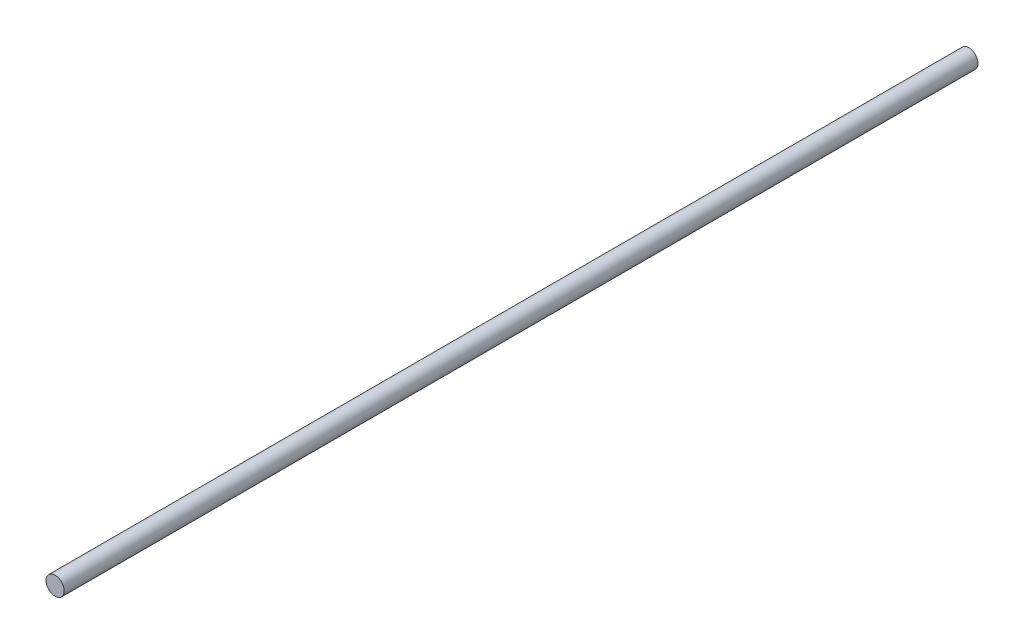
SolidWorks part; units mm, degrees
ref_plane "Front Plane" through (0, 0, 0) normal (0, 0, 1) x (1, 0, 0)
ref_plane "Top Plane" through (0, 0, 0) normal (0, 1, 0) x (1, 0, 0)
ref_plane "Right Plane" through (0, 0, 0) normal (1, 0, 0) x (0, 0, -1)
sketch "Sketch1" plane through (0, 0, 0) normal (0, 0, 1) x (1, 0, 0)
  circle A0 centre (0, 0) radius 15
  dimension "D1" = 30
extrude "Boss-Extrude1" add sketch "Sketch1" along normal blind 1500
